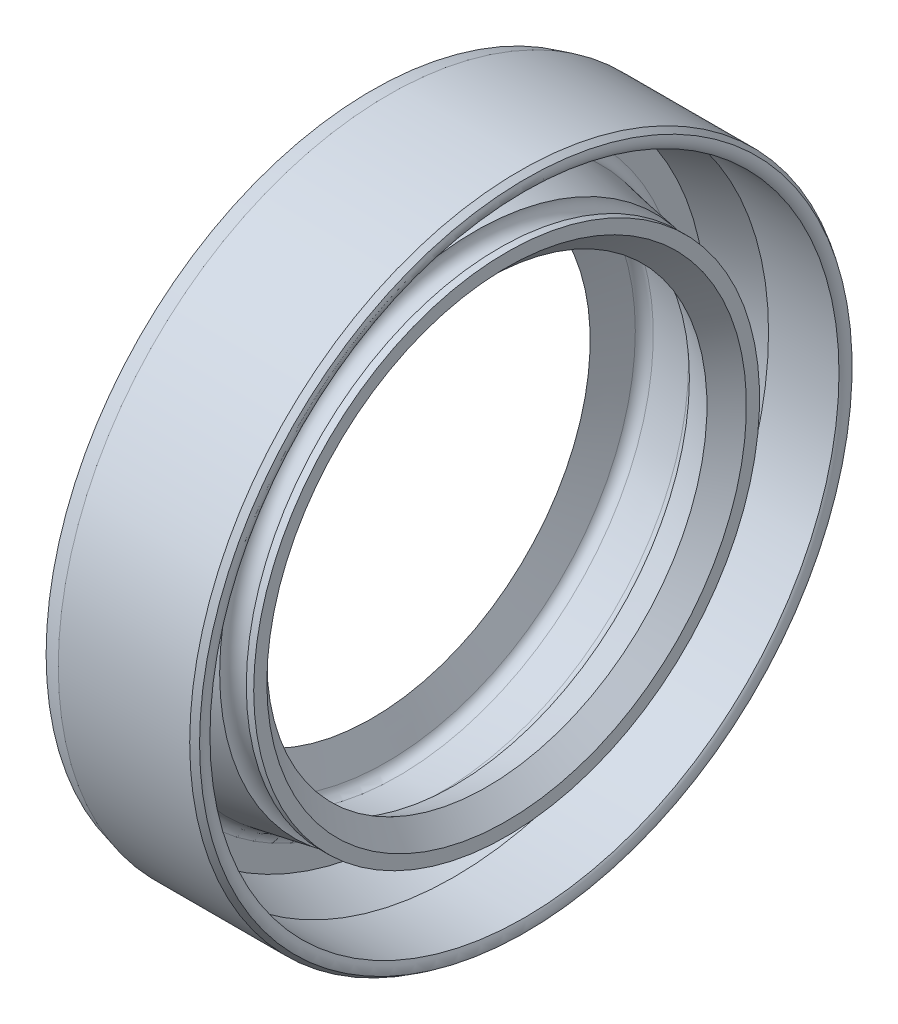
SolidWorks part; units mm, degrees
material "NBR"
ref_plane "Horní rovina" through (0, 0, 0) normal (0, 0, 1) x (1, 0, 0)
ref_plane "Přední rovina" through (0, 0, 0) normal (0, 1, 0) x (1, 0, 0)
ref_plane "Pravá rovina" through (0, 0, 0) normal (1, 0, 0) x (0, 0, -1)
sketch "Skica1" plane through (0, 0, 0) normal (0, 1, 0) x (1, 0, 0)
  line L0 (0.7524, 15) -> (0, 14.7998)
  line L1 (6.7255, 15) -> (0.7524, 15)
  line L2 (7, 14.8267) -> (6.7255, 15)
  line L3 (6.939, 14.2929) -> (3.7364, 14.2929)
  line L4 (3.7364, 14.2929) -> (1.4946, 13.6922)
  line L5 (1.4946, 13.6922) -> (1.4946, 12.6026)
  line L6 (4.6793, 11.5932) -> (1.9356, 12.077)
  line L7 (6.1277, 11.4946) -> (5.7914, 11.4946)
  line L8 (6.1277, 10.8967) -> (6.1277, 11.4946)
  line L9 (6.1277, 10.8967) -> (5.231, 10)
  line L10 (5.231, 10) -> (3.7364, 10.6969)
  line L11 (3.1413, 11.2512) -> (1.1985, 11.5938)
  line L12 (0, 14.7998) -> (0, 12.253)
  line L13 (0, 0) -> (0, 15.1997) construction
  line L14 (5.231, 10) -> (-0.9026, 10) construction
  line L16 (-19.4566, 0) -> (20.6518, 0) construction
  line L17 (0, 12.253) -> (0, 9.9247)
  line L18 (0, 9.9247) -> (0.6599, 11.3157)
  arc A0 (6.939, 14.2929) -> (7, 14.8267) centre (6.5112, 14.6121) ccw
  arc A1 (1.4946, 12.6026) -> (1.9356, 12.077) centre (2.0283, 12.6026) ccw
  arc A3 (3.7364, 10.6969) -> (3.1413, 11.2512) centre (3.0115, 10.5153) ccw
  arc A5 (0.6599, 11.3157) -> (1.1985, 11.5938) centre (1.1116, 11.1014) cw
  arc A6 (4.6793, 11.5932) -> (5.7914, 11.4946) centre (5.2309, 11.4935) ccw
  dimension "D10" = 0.5
  dimension "D2" = 110
  dimension "D3" = 1.2682
  dimension "D4" = 1.6491
  dimension "D5" = 0.5978
  dimension "D6" = 0.3363
  dimension "D8" = 10
  dimension "D9" = 15
  dimension "D12" = 7
  dimension "D13" = 12.253
revolve "Rotovat1" add sketch "Skica1" angle 360 about L16
